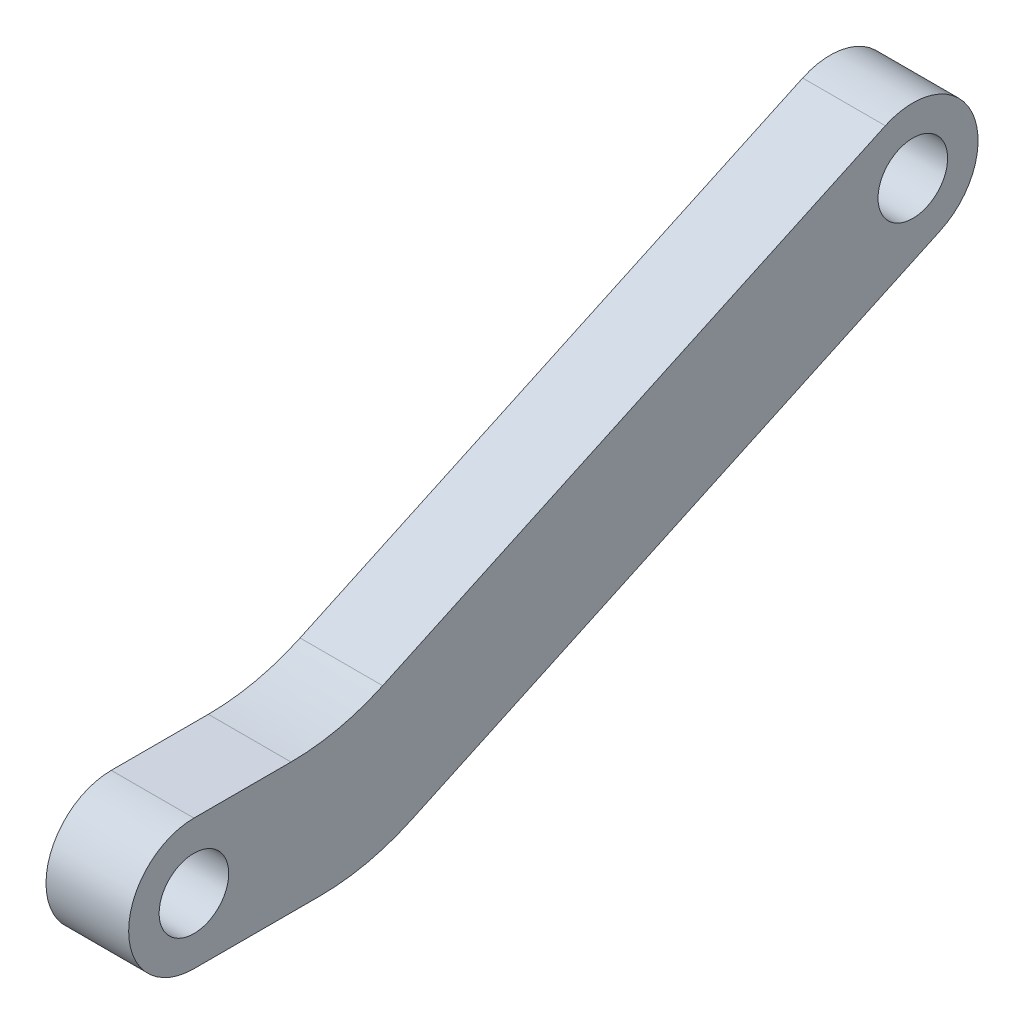
SolidWorks part; units mm, degrees
ref_plane "Front Plane" through (0, 0, 0) normal (0, 0, 1) x (1, 0, 0)
ref_plane "Top Plane" through (0, 0, 0) normal (0, 1, 0) x (1, 0, 0)
ref_plane "Right Plane" through (0, 0, 0) normal (1, 0, 0) x (0, 0, -1)
sketch "Sketch1" plane through (0, 0, 0) normal (1, 0, 0) x (0, 0, -1)
  line L0 (0, 0) -> (33.05, 11.95) construction
  line L1 (0, -3) -> (5.7898, -3)
  line L2 (0, 3) -> (4.4637, 3)
  line L7 (10.0043, -2.0685) -> (34.3144, 9.2294)
  line L8 (8.6782, 3.9315) -> (31.7856, 14.6706)
  circle A0 centre (0, 0) radius 1.6
  circle A1 centre (33.05, 11.95) radius 1.6
  arc A2 (0, 3) -> (0, -3) centre (0, 0) ccw
  arc A8 (34.3144, 9.2294) -> (31.7856, 14.6706) centre (33.05, 11.95) ccw
  arc A9 (5.7898, -3) -> (10.0043, -2.0685) centre (5.7898, 7) ccw
  arc A10 (4.4637, 3) -> (8.6782, 3.9315) centre (4.4637, 13) ccw
  point P18 (8, -3)
  dimension "D3" = 3.2
  dimension "D4" = 6
  dimension "D6" = 10
  dimension "D1" = 33.05
  dimension "D2" = 11.95
  dimension "D5" = 8
extrude "Boss-Extrude1" add sketch "Sketch1" along normal mid plane 3.8
